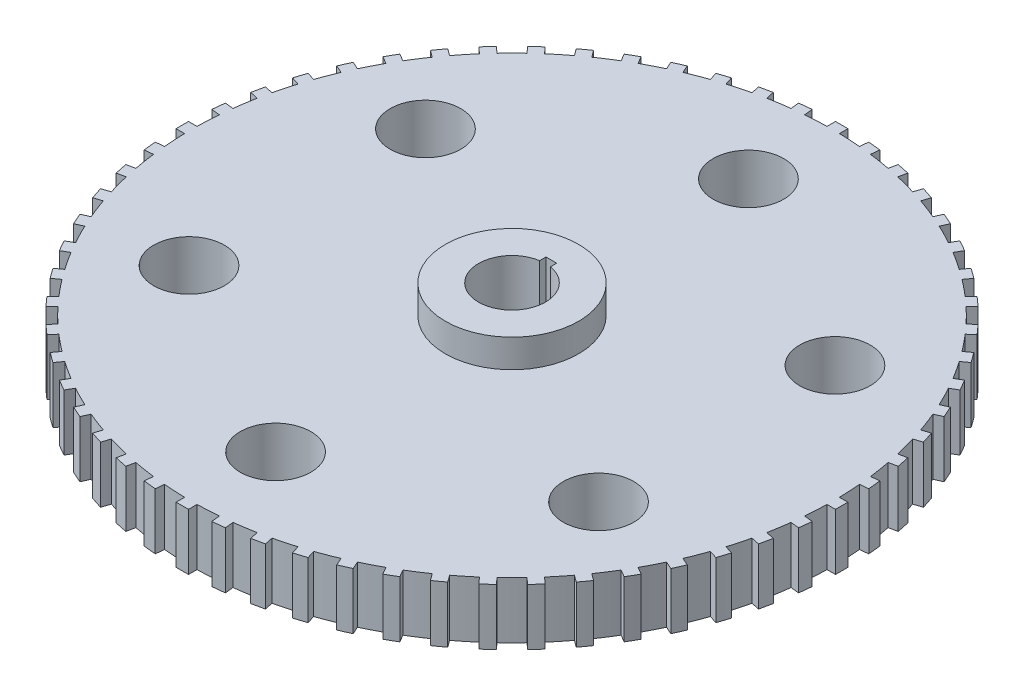
SolidWorks part; units mm, degrees
ref_plane "Front Plane" through (0, 0, 0) normal (0, 0, 1) x (1, 0, 0)
ref_plane "Top Plane" through (0, 0, 0) normal (0, 1, 0) x (1, 0, 0)
ref_plane "Right Plane" through (0, 0, 0) normal (1, 0, 0) x (0, 0, -1)
sketch "Sketch1" plane through (0, 0, 0) normal (0, 1, 0) x (1, 0, 0)
  line L0 (-1.397, -72.2495) -> (-1.397, -74.1548)
  line L1 (1.397, -72.2495) -> (1.397, -74.1548)
  line L6 (-8.9415, -71.7077) -> (-9.1406, -73.6026)
  line L7 (-6.1628, -71.9997) -> (-6.3619, -73.8946)
  line L8 (-16.388, -70.3802) -> (-16.7841, -72.2439)
  line L9 (-13.655, -70.9611) -> (-14.0512, -72.8248)
  line L10 (-23.6549, -68.2817) -> (-24.2437, -70.0937)
  line L11 (-20.9977, -69.145) -> (-21.5865, -70.9571)
  line L12 (-30.6627, -65.435) -> (-31.4377, -67.1756)
  line L13 (-28.1103, -66.5714) -> (-28.8853, -68.312)
  line L14 (-37.3346, -61.8714) -> (-38.2873, -63.5215)
  line L15 (-34.9149, -63.2684) -> (-35.8676, -64.9185)
  line L16 (-43.5974, -57.6299) -> (-44.7173, -59.1714)
  line L17 (-41.337, -59.2722) -> (-42.4569, -60.8137)
  line L18 (-49.3825, -52.7571) -> (-50.6574, -54.173)
  line L19 (-47.3062, -54.6266) -> (-48.5811, -56.0426)
  line L20 (-54.6266, -47.3062) -> (-56.0426, -48.5811)
  line L21 (-52.7571, -49.3825) -> (-54.173, -50.6574)
  line L22 (-59.2722, -41.337) -> (-60.8137, -42.4569)
  line L23 (-57.6299, -43.5974) -> (-59.1714, -44.7173)
  line L24 (-63.2684, -34.9149) -> (-64.9185, -35.8676)
  line L25 (-61.8714, -37.3346) -> (-63.5215, -38.2873)
  line L26 (-66.5714, -28.1103) -> (-68.312, -28.8853)
  line L27 (-65.435, -30.6627) -> (-67.1756, -31.4377)
  line L28 (-69.145, -20.9977) -> (-70.9571, -21.5865)
  line L29 (-68.2817, -23.6549) -> (-70.0937, -24.2437)
  line L30 (-70.9611, -13.655) -> (-72.8248, -14.0512)
  line L31 (-70.3802, -16.388) -> (-72.2439, -16.7841)
  line L32 (-71.9997, -6.1628) -> (-73.8946, -6.3619)
  line L33 (-71.7077, -8.9415) -> (-73.6026, -9.1406)
  line L34 (-72.2495, 1.397) -> (-74.1548, 1.397)
  line L35 (-72.2495, -1.397) -> (-74.1548, -1.397)
  line L36 (-71.7077, 8.9415) -> (-73.6026, 9.1406)
  line L37 (-71.9997, 6.1628) -> (-73.8946, 6.3619)
  line L38 (-70.3802, 16.388) -> (-72.2439, 16.7841)
  line L39 (-70.9611, 13.655) -> (-72.8248, 14.0512)
  line L40 (-68.2817, 23.6549) -> (-70.0937, 24.2437)
  line L41 (-69.145, 20.9977) -> (-70.9571, 21.5865)
  line L42 (-65.435, 30.6627) -> (-67.1756, 31.4377)
  line L43 (-66.5714, 28.1103) -> (-68.312, 28.8853)
  line L44 (-61.8714, 37.3346) -> (-63.5215, 38.2873)
  line L45 (-63.2684, 34.9149) -> (-64.9185, 35.8676)
  line L46 (-57.6299, 43.5974) -> (-59.1714, 44.7173)
  line L47 (-59.2722, 41.337) -> (-60.8137, 42.4569)
  line L48 (-52.7571, 49.3825) -> (-54.173, 50.6574)
  line L49 (-54.6266, 47.3062) -> (-56.0426, 48.5811)
  line L50 (-47.3062, 54.6266) -> (-48.5811, 56.0426)
  line L51 (-49.3825, 52.7571) -> (-50.6574, 54.173)
  line L52 (-41.337, 59.2722) -> (-42.4569, 60.8137)
  line L53 (-43.5974, 57.6299) -> (-44.7173, 59.1714)
  line L54 (-34.9149, 63.2684) -> (-35.8676, 64.9185)
  line L55 (-37.3346, 61.8714) -> (-38.2873, 63.5215)
  line L56 (-28.1103, 66.5714) -> (-28.8853, 68.312)
  line L57 (-30.6627, 65.435) -> (-31.4377, 67.1756)
  line L58 (-20.9977, 69.145) -> (-21.5865, 70.9571)
  line L59 (-23.6549, 68.2817) -> (-24.2437, 70.0937)
  line L60 (-13.655, 70.9611) -> (-14.0512, 72.8248)
  line L61 (-16.388, 70.3802) -> (-16.7841, 72.2439)
  line L62 (-6.1628, 71.9997) -> (-6.3619, 73.8946)
  line L63 (-8.9415, 71.7077) -> (-9.1406, 73.6026)
  line L64 (1.397, 72.2495) -> (1.397, 74.1548)
  line L65 (-1.397, 72.2495) -> (-1.397, 74.1548)
  line L66 (8.9415, 71.7077) -> (9.1406, 73.6026)
  line L67 (6.1628, 71.9997) -> (6.3619, 73.8946)
  line L68 (16.388, 70.3802) -> (16.7841, 72.2439)
  line L69 (13.655, 70.9611) -> (14.0512, 72.8248)
  line L70 (23.6549, 68.2817) -> (24.2437, 70.0937)
  line L71 (20.9977, 69.145) -> (21.5865, 70.9571)
  line L72 (30.6627, 65.435) -> (31.4377, 67.1756)
  line L73 (28.1103, 66.5714) -> (28.8853, 68.312)
  line L74 (37.3346, 61.8714) -> (38.2873, 63.5215)
  line L75 (34.9149, 63.2684) -> (35.8676, 64.9185)
  line L76 (43.5974, 57.6299) -> (44.7173, 59.1714)
  line L77 (41.337, 59.2722) -> (42.4569, 60.8137)
  line L78 (49.3825, 52.7571) -> (50.6574, 54.173)
  line L79 (47.3062, 54.6266) -> (48.5811, 56.0426)
  line L80 (54.6266, 47.3062) -> (56.0426, 48.5811)
  line L81 (52.7571, 49.3825) -> (54.173, 50.6574)
  line L82 (59.2722, 41.337) -> (60.8137, 42.4569)
  line L83 (57.6299, 43.5974) -> (59.1714, 44.7173)
  line L84 (63.2684, 34.9149) -> (64.9185, 35.8676)
  line L85 (61.8714, 37.3346) -> (63.5215, 38.2873)
  line L86 (66.5714, 28.1103) -> (68.312, 28.8853)
  line L87 (65.435, 30.6627) -> (67.1756, 31.4377)
  line L88 (69.145, 20.9977) -> (70.9571, 21.5865)
  line L89 (68.2817, 23.6549) -> (70.0937, 24.2437)
  line L90 (70.9611, 13.655) -> (72.8248, 14.0512)
  line L91 (70.3802, 16.388) -> (72.2439, 16.7841)
  line L92 (71.9997, 6.1628) -> (73.8946, 6.3619)
  line L93 (71.7077, 8.9415) -> (73.6026, 9.1406)
  line L94 (72.2495, -1.397) -> (74.1548, -1.397)
  line L95 (72.2495, 1.397) -> (74.1548, 1.397)
  line L96 (71.7077, -8.9415) -> (73.6026, -9.1406)
  line L97 (71.9997, -6.1628) -> (73.8946, -6.3619)
  line L98 (70.3802, -16.388) -> (72.2439, -16.7841)
  line L99 (70.9611, -13.655) -> (72.8248, -14.0512)
  line L100 (68.2817, -23.6549) -> (70.0937, -24.2437)
  line L101 (69.145, -20.9977) -> (70.9571, -21.5865)
  line L102 (65.435, -30.6627) -> (67.1756, -31.4377)
  line L103 (66.5714, -28.1103) -> (68.312, -28.8853)
  line L104 (61.8714, -37.3346) -> (63.5215, -38.2873)
  line L105 (63.2684, -34.9149) -> (64.9185, -35.8676)
  line L106 (57.6299, -43.5974) -> (59.1714, -44.7173)
  line L107 (59.2722, -41.337) -> (60.8137, -42.4569)
  line L108 (52.7571, -49.3825) -> (54.173, -50.6574)
  line L109 (54.6266, -47.3062) -> (56.0426, -48.5811)
  line L110 (47.3062, -54.6266) -> (48.5811, -56.0426)
  line L111 (49.3825, -52.7571) -> (50.6574, -54.173)
  line L112 (41.337, -59.2722) -> (42.4569, -60.8137)
  line L113 (43.5974, -57.6299) -> (44.7173, -59.1714)
  line L114 (34.9149, -63.2684) -> (35.8676, -64.9185)
  line L115 (37.3346, -61.8714) -> (38.2873, -63.5215)
  line L116 (28.1103, -66.5714) -> (28.8853, -68.312)
  line L117 (30.6627, -65.435) -> (31.4377, -67.1756)
  line L118 (20.9977, -69.145) -> (21.5865, -70.9571)
  line L119 (23.6549, -68.2817) -> (24.2437, -70.0937)
  line L120 (13.655, -70.9611) -> (14.0512, -72.8248)
  line L121 (16.388, -70.3802) -> (16.7841, -72.2439)
  line L122 (6.1628, -71.9997) -> (6.3619, -73.8946)
  line L123 (8.9415, -71.7077) -> (9.1406, -73.6026)
  line L124 (-1.2065, -7.4338) -> (-1.2065, -7.5311)
  line L125 (-1.2065, 8.8519) -> (1.2065, 8.8519)
  line L126 (-1.2065, 8.8519) -> (-1.2065, 7.4338)
  line L127 (-1.2065, -7.5311) -> (1.2065, -7.5311) construction
  line L128 (1.2065, 8.8519) -> (1.2065, 7.4338)
  line L129 (1.2065, -7.4338) -> (1.2065, -7.5311)
  arc A0 (1.397, -72.2495) -> (6.1628, -71.9997) centre (0, 0) ccw
  arc A1 (-1.397, -74.1548) -> (1.397, -74.1548) centre (0, 0) ccw
  arc A2 (-9.1406, -73.6026) -> (-6.3619, -73.8946) centre (0, 0) ccw
  arc A3 (-16.7841, -72.2439) -> (-14.0512, -72.8248) centre (0, 0) ccw
  arc A4 (-24.2437, -70.0937) -> (-21.5865, -70.9571) centre (0, 0) ccw
  arc A5 (-31.4377, -67.1756) -> (-28.8853, -68.312) centre (0, 0) ccw
  arc A6 (-38.2873, -63.5215) -> (-35.8676, -64.9185) centre (0, 0) ccw
  arc A7 (-44.7173, -59.1714) -> (-42.4569, -60.8137) centre (0, 0) ccw
  arc A8 (-50.6574, -54.173) -> (-48.5811, -56.0426) centre (0, 0) ccw
  arc A9 (-56.0426, -48.5811) -> (-54.173, -50.6574) centre (0, 0) ccw
  arc A10 (-60.8137, -42.4569) -> (-59.1714, -44.7173) centre (0, 0) ccw
  arc A11 (-64.9185, -35.8676) -> (-63.5215, -38.2873) centre (0, 0) ccw
  arc A12 (-68.312, -28.8853) -> (-67.1756, -31.4377) centre (0, 0) ccw
  arc A13 (-70.9571, -21.5865) -> (-70.0937, -24.2437) centre (0, 0) ccw
  arc A14 (-72.8248, -14.0512) -> (-72.2439, -16.7841) centre (0, 0) ccw
  arc A15 (-73.8946, -6.3619) -> (-73.6026, -9.1406) centre (0, 0) ccw
  arc A16 (-74.1548, 1.397) -> (-74.1548, -1.397) centre (0, 0) ccw
  arc A17 (-73.6026, 9.1406) -> (-73.8946, 6.3619) centre (0, 0) ccw
  arc A18 (-72.2439, 16.7841) -> (-72.8248, 14.0512) centre (0, 0) ccw
  arc A19 (-70.0937, 24.2437) -> (-70.9571, 21.5865) centre (0, 0) ccw
  arc A20 (-67.1756, 31.4377) -> (-68.312, 28.8853) centre (0, 0) ccw
  arc A21 (-63.5215, 38.2873) -> (-64.9185, 35.8676) centre (0, 0) ccw
  arc A22 (-59.1714, 44.7173) -> (-60.8137, 42.4569) centre (0, 0) ccw
  arc A23 (-54.173, 50.6574) -> (-56.0426, 48.5811) centre (0, 0) ccw
  arc A24 (-48.5811, 56.0426) -> (-50.6574, 54.173) centre (0, 0) ccw
  arc A25 (-42.4569, 60.8137) -> (-44.7173, 59.1714) centre (0, 0) ccw
  arc A26 (-35.8676, 64.9185) -> (-38.2873, 63.5215) centre (0, 0) ccw
  arc A27 (-28.8853, 68.312) -> (-31.4377, 67.1756) centre (0, 0) ccw
  arc A28 (-21.5865, 70.9571) -> (-24.2437, 70.0937) centre (0, 0) ccw
  arc A29 (-14.0512, 72.8248) -> (-16.7841, 72.2439) centre (0, 0) ccw
  arc A30 (-6.3619, 73.8946) -> (-9.1406, 73.6026) centre (0, 0) ccw
  arc A31 (1.397, 74.1548) -> (-1.397, 74.1548) centre (0, 0) ccw
  arc A32 (9.1406, 73.6026) -> (6.3619, 73.8946) centre (0, 0) ccw
  arc A33 (16.7841, 72.2439) -> (14.0512, 72.8248) centre (0, 0) ccw
  arc A34 (24.2437, 70.0937) -> (21.5865, 70.9571) centre (0, 0) ccw
  arc A35 (31.4377, 67.1756) -> (28.8853, 68.312) centre (0, 0) ccw
  arc A36 (38.2873, 63.5215) -> (35.8676, 64.9185) centre (0, 0) ccw
  arc A37 (44.7173, 59.1714) -> (42.4569, 60.8137) centre (0, 0) ccw
  arc A38 (50.6574, 54.173) -> (48.5811, 56.0426) centre (0, 0) ccw
  arc A39 (56.0426, 48.5811) -> (54.173, 50.6574) centre (0, 0) ccw
  arc A40 (60.8137, 42.4569) -> (59.1714, 44.7173) centre (0, 0) ccw
  arc A41 (64.9185, 35.8676) -> (63.5215, 38.2873) centre (0, 0) ccw
  arc A42 (68.312, 28.8853) -> (67.1756, 31.4377) centre (0, 0) ccw
  arc A43 (70.9571, 21.5865) -> (70.0937, 24.2437) centre (0, 0) ccw
  arc A44 (72.8248, 14.0512) -> (72.2439, 16.7841) centre (0, 0) ccw
  arc A45 (73.8946, 6.3619) -> (73.6026, 9.1406) centre (0, 0) ccw
  arc A46 (74.1548, -1.397) -> (74.1548, 1.397) centre (0, 0) ccw
  arc A47 (73.6026, -9.1406) -> (73.8946, -6.3619) centre (0, 0) ccw
  arc A48 (72.2439, -16.7841) -> (72.8248, -14.0512) centre (0, 0) ccw
  arc A49 (70.0937, -24.2437) -> (70.9571, -21.5865) centre (0, 0) ccw
  arc A50 (67.1756, -31.4377) -> (68.312, -28.8853) centre (0, 0) ccw
  arc A51 (63.5215, -38.2873) -> (64.9185, -35.8676) centre (0, 0) ccw
  arc A52 (59.1714, -44.7173) -> (60.8137, -42.4569) centre (0, 0) ccw
  arc A53 (54.173, -50.6574) -> (56.0426, -48.5811) centre (0, 0) ccw
  arc A54 (48.5811, -56.0426) -> (50.6574, -54.173) centre (0, 0) ccw
  arc A55 (42.4569, -60.8137) -> (44.7173, -59.1714) centre (0, 0) ccw
  arc A56 (35.8676, -64.9185) -> (38.2873, -63.5215) centre (0, 0) ccw
  arc A57 (28.8853, -68.312) -> (31.4377, -67.1756) centre (0, 0) ccw
  arc A58 (21.5865, -70.9571) -> (24.2437, -70.0937) centre (0, 0) ccw
  arc A59 (14.0512, -72.8248) -> (16.7841, -72.2439) centre (0, 0) ccw
  arc A60 (6.3619, -73.8946) -> (9.1406, -73.6026) centre (0, 0) ccw
  arc A61 (-1.2065, 7.4338) -> (1.2065, 7.4338) centre (0, 0) ccw
  arc A62 (8.9415, -71.7077) -> (13.655, -70.9611) centre (0, 0) ccw
  arc A63 (16.388, -70.3802) -> (20.9977, -69.145) centre (0, 0) ccw
  arc A64 (23.6549, -68.2817) -> (28.1103, -66.5714) centre (0, 0) ccw
  arc A65 (30.6627, -65.435) -> (34.9149, -63.2684) centre (0, 0) ccw
  arc A66 (37.3346, -61.8714) -> (41.337, -59.2722) centre (0, 0) ccw
  arc A67 (43.5974, -57.6299) -> (47.3062, -54.6266) centre (0, 0) ccw
  arc A68 (49.3825, -52.7571) -> (52.7571, -49.3825) centre (0, 0) ccw
  arc A69 (54.6266, -47.3062) -> (57.6299, -43.5974) centre (0, 0) ccw
  arc A70 (59.2722, -41.337) -> (61.8714, -37.3346) centre (0, 0) ccw
  arc A71 (63.2684, -34.9149) -> (65.435, -30.6627) centre (0, 0) ccw
  arc A72 (66.5714, -28.1103) -> (68.2817, -23.6549) centre (0, 0) ccw
  arc A73 (69.145, -20.9977) -> (70.3802, -16.388) centre (0, 0) ccw
  arc A74 (70.9611, -13.655) -> (71.7077, -8.9415) centre (0, 0) ccw
  arc A75 (71.9997, -6.1628) -> (72.2495, -1.397) centre (0, 0) ccw
  arc A76 (71.7077, 8.9415) -> (70.9611, 13.655) centre (0, 0) ccw
  arc A77 (70.3802, 16.388) -> (69.145, 20.9977) centre (0, 0) ccw
  arc A78 (68.2817, 23.6549) -> (66.5714, 28.1103) centre (0, 0) ccw
  arc A79 (65.435, 30.6627) -> (63.2684, 34.9149) centre (0, 0) ccw
  arc A80 (61.8714, 37.3346) -> (59.2722, 41.337) centre (0, 0) ccw
  arc A81 (57.6299, 43.5974) -> (54.6266, 47.3062) centre (0, 0) ccw
  arc A82 (52.7571, 49.3825) -> (49.3825, 52.7571) centre (0, 0) ccw
  arc A83 (47.3062, 54.6266) -> (43.5974, 57.6299) centre (0, 0) ccw
  arc A84 (41.337, 59.2722) -> (37.3346, 61.8714) centre (0, 0) ccw
  arc A85 (34.9149, 63.2684) -> (30.6627, 65.435) centre (0, 0) ccw
  arc A86 (28.1103, 66.5714) -> (23.6549, 68.2817) centre (0, 0) ccw
  arc A87 (20.9977, 69.145) -> (16.388, 70.3802) centre (0, 0) ccw
  arc A88 (6.1628, 71.9997) -> (1.397, 72.2495) centre (0, 0) ccw
  arc A89 (-1.397, 72.2495) -> (-6.1628, 71.9997) centre (0, 0) ccw
  arc A90 (-8.9415, 71.7077) -> (-13.655, 70.9611) centre (0, 0) ccw
  arc A91 (-16.388, 70.3802) -> (-20.9977, 69.145) centre (0, 0) ccw
  arc A92 (-23.6549, 68.2817) -> (-28.1103, 66.5714) centre (0, 0) ccw
  arc A93 (-30.6627, 65.435) -> (-34.9149, 63.2684) centre (0, 0) ccw
  arc A94 (-37.3346, 61.8714) -> (-41.337, 59.2722) centre (0, 0) ccw
  arc A95 (-43.5974, 57.6299) -> (-47.3062, 54.6266) centre (0, 0) ccw
  arc A96 (-49.3825, 52.7571) -> (-52.7571, 49.3825) centre (0, 0) ccw
  arc A97 (-54.6266, 47.3062) -> (-57.6299, 43.5974) centre (0, 0) ccw
  arc A98 (-59.2722, 41.337) -> (-61.8714, 37.3346) centre (0, 0) ccw
  arc A99 (-63.2684, 34.9149) -> (-65.435, 30.6627) centre (0, 0) ccw
  arc A100 (-66.5714, 28.1103) -> (-68.2817, 23.6549) centre (0, 0) ccw
  arc A101 (-69.145, 20.9977) -> (-70.3802, 16.388) centre (0, 0) ccw
  arc A102 (-70.9611, 13.655) -> (-71.7077, 8.9415) centre (0, 0) ccw
  arc A103 (-71.9997, 6.1628) -> (-72.2495, 1.397) centre (0, 0) ccw
  arc A104 (-72.2495, -1.397) -> (-71.9997, -6.1628) centre (0, 0) ccw
  arc A105 (-71.7077, -8.9415) -> (-70.9611, -13.655) centre (0, 0) ccw
  arc A106 (-70.3802, -16.388) -> (-69.145, -20.9977) centre (0, 0) ccw
  arc A107 (-68.2817, -23.6549) -> (-66.5714, -28.1103) centre (0, 0) ccw
  arc A108 (-65.435, -30.6627) -> (-63.2684, -34.9149) centre (0, 0) ccw
  arc A109 (-61.8714, -37.3346) -> (-59.2722, -41.337) centre (0, 0) ccw
  arc A110 (-57.6299, -43.5974) -> (-54.6266, -47.3062) centre (0, 0) ccw
  arc A111 (-52.7571, -49.3825) -> (-49.3825, -52.7571) centre (0, 0) ccw
  arc A112 (-47.3062, -54.6266) -> (-43.5974, -57.6299) centre (0, 0) ccw
  arc A113 (-41.337, -59.2722) -> (-37.3346, -61.8714) centre (0, 0) ccw
  arc A114 (-34.9149, -63.2684) -> (-30.6627, -65.435) centre (0, 0) ccw
  arc A115 (-28.1103, -66.5714) -> (-23.6549, -68.2817) centre (0, 0) ccw
  arc A116 (-20.9977, -69.145) -> (-16.388, -70.3802) centre (0, 0) ccw
  arc A117 (-13.655, -70.9611) -> (-8.9415, -71.7077) centre (0, 0) ccw
  arc A118 (-6.1628, -71.9997) -> (-1.397, -72.2495) centre (0, 0) ccw
  arc A119 (72.2495, 1.397) -> (71.9997, 6.1628) centre (0, 0) ccw
  arc A120 (13.655, 70.9611) -> (8.9415, 71.7077) centre (0, 0) ccw
  point P6 (0, -73.041)
  point P245 (0, 0)
  dimension "D1" = 144.526
  dimension "D2" = 148.336
  dimension "D4" = 15.0622
  dimension "D3" = 60
  dimension "D5" = 2.413
  dimension "D6" = 16.383
extrude "Boss-Extrude4" add sketch "Sketch1" along normal blind 12.7 contours L69 A120 L66 A32 L67 A88 L64 A31 L65 A89 L62 A30 L63 A90 L60 A29 L61 A91 L58 A28 L59 A92 L56 A27 L57 A93 L54 A26 L55 A94 L52 A25 L53 A95 L50 A24 L51 A96 L48 A23 L49 A97 L46 A22 L47 A98 L44 A21 L45 A99 L42 | A61 L128 L125 L126
sketch "Sketch2" plane through (0, 12.7, 0) normal (0, 1, 0) x (1, 0, 0)
  line L0 (-1.2065, 7.4338) -> (-1.2065, 8.8519)
  line L1 (-1.2065, 8.8519) -> (1.2065, 8.8519)
  line L2 (1.2065, 8.8519) -> (1.2065, 7.4338)
  circle A0 centre (0, 0) radius 14.986
  arc A1 (-1.2065, 7.4338) -> (1.2065, 7.4338) centre (0, 0) ccw
  dimension "D1" = 29.972
extrude "Boss-Extrude5" add sketch "Sketch2" along normal blind 6.35 contours A0
sketch "Sketch3" plane through (0, 12.7, 0) normal (0, 1, 0) x (1, 0, 0)
  circle A0 centre (0, 53.1876) radius 7.9375
  arc A1 (-1.2065, 7.4338) -> (1.2065, 7.4338) centre (0, 0) ccw construction
  circle A2 centre (46.0618, 26.5938) radius 7.9375
  circle A3 centre (46.0618, -26.5938) radius 7.9375
  circle A4 centre (0, -53.1876) radius 7.9375
  circle A5 centre (-46.0618, -26.5938) radius 7.9375
  circle A6 centre (-46.0618, 26.5938) radius 7.9375
  point P17 (0, 0)
  dimension "D1" = 53.1876
  dimension "D2" = 15.875
  dimension "D3" = 6
extrude "Cut-Extrude1" cut sketch "Sketch3" against normal up to surface (12.7 mm away) up to face at (0, 0, -0.3302)
